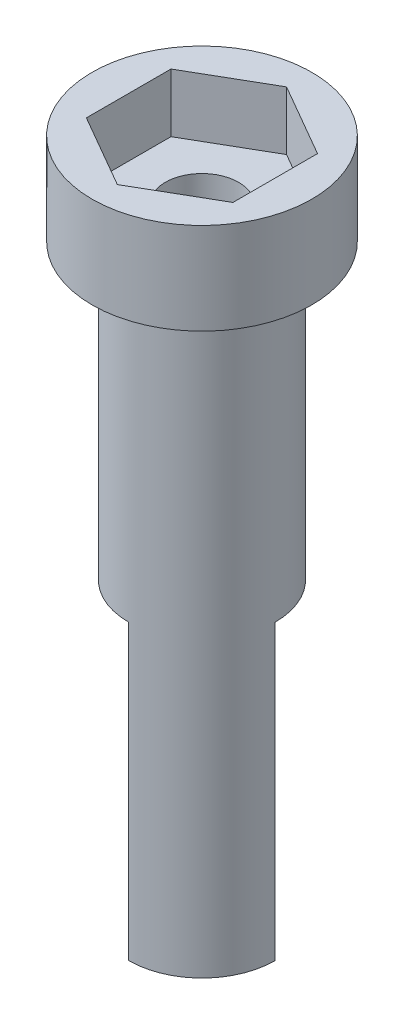
SolidWorks part; units mm, degrees
ref_plane "前视基准面" through (0, 0, 0) normal (0, 0, 1) x (1, 0, 0)
ref_plane "上视基准面" through (0, 0, 0) normal (0, 1, 0) x (1, 0, 0)
ref_plane "右视基准面" through (0, 0, 0) normal (1, 0, 0) x (0, 0, -1)
other "Configuration Table"
sketch "草图1" plane through (0, 0, 0) normal (0, 1, 0) x (1, 0, 0)
  circle A0 centre (0, 0) radius 2
  circle A1 centre (0, 0) radius 1
  dimension "D1" = 4
  dimension "D2" = 2
extrude "凸台-拉伸1" add sketch "草图1" along normal blind 29
sketch "草图2" plane through (0, 0, 0) normal (0, 1, 0) x (1, 0, 0)
  circle A0 centre (0, 0) radius 3
  circle A2 centre (0, 0) radius 2
  circle A3 centre (0, 0) radius 2
  dimension "D2" = 6
  dimension "D1" = 0
extrude "凸台-拉伸2" add sketch "草图2" along normal blind 2.5
sketch "草图3" plane through (0, 0, 0) normal (0, 1, 0) x (1, 0, 0)
  circle A1 centre (0, 0) radius 2
  circle A2 centre (0, 0) radius 2
  circle A3 centre (0, 0) radius 3
  circle A4 centre (0, 0) radius 3
  dimension "D1" = 0
  dimension "D2" = 0
extrude "凸台-拉伸3" add sketch "草图3" against normal blind 2.5 from surface at 29 starting at face at (0, 29, 2)
sketch "草图4" plane through (0, 0, 0) normal (0, 1, 0) x (1, 0, 0)
  circle A0 centre (0, 0) radius 1.6
  dimension "D1" = 3.2
extrude "切除-拉伸1" cut sketch "草图4" along normal blind 1.5
sketch "草图5" plane through (0, 0, 0) normal (0, 1, 0) x (1, 0, 0)
  line L1 (0, -2.3094) -> (2, -1.1547)
  line L2 (2, -1.1547) -> (2, 1.1547)
  line L3 (2, 1.1547) -> (0, 2.3094)
  line L4 (0, 2.3094) -> (-2, 1.1547)
  line L5 (-2, 1.1547) -> (-2, -1.1547)
  line L6 (-2, -1.1547) -> (0, -2.3094)
  circle A0 centre (0, 0) radius 2 construction
  dimension "D1" = 4
extrude "切除-拉伸2" cut sketch "草图5" against normal blind 1.6 from surface at 29 starting at face at (0, 29, 1)
sketch "草图7" plane through (0, 0, 0) normal (0, 1, 0) x (1, 0, 0)
  circle A1 centre (0, 0) radius 3
  circle A2 centre (0, 0) radius 3
  dimension "D1" = 0
extrude "切除-拉伸3" cut sketch "草图7" along normal blind 10.5
sketch "草图8" plane through (0, 0, 0) normal (0, 1, 0) x (1, 0, 0)
  line L0 (2, 0) -> (-2, 0)
  line L1 (0, -2) -> (0, 2)
  circle A1 centre (0, 0) radius 2
  circle A2 centre (0, 0) radius 2
  dimension "D1" = 0
extrude "切除-拉伸4" cut sketch "草图8" along normal blind 8 from surface at 10.5 contours L0 A2 L1 | L0 A2 L1
